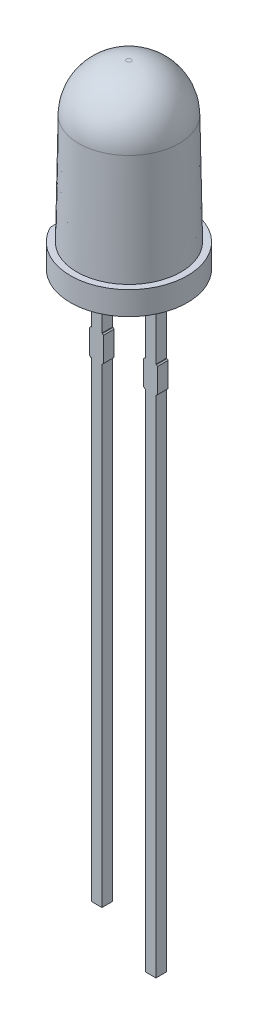
SolidWorks part; units mm, degrees
ref_plane "Front Plane" through (0, 0, 0) normal (0, 0, 1) x (1, 0, 0)
ref_plane "Top Plane" through (0, 0, 0) normal (0, 1, 0) x (1, 0, 0)
ref_plane "Right Plane" through (0, 0, 0) normal (1, 0, 0) x (0, 0, -1)
sketch "Sketch1" plane through (0, 0, 0) normal (0, 1, 0) x (1, 0, 0)
  circle A0 centre (0, 0) radius 2.75
  dimension "D1" = 5.5
extrude "Boss-Extrude1" add sketch "Sketch1" along normal blind 1.1 contours A0
sketch "Sketch2" plane through (0, 1.1, 0) normal (0, 1, 0) x (1, 0, 0)
  circle A0 centre (0, 0) radius 2.45
  dimension "D1" = 4.9
ref_plane "Plane1" through (0, 8.5, 0) normal (0, -1, 0) x (-1, 0, 0)
sketch "Sketch3" plane through (0, 0, 0) normal (0, 0, 1) x (1, 0, 0)
  line L0 (0, 1.1) -> (0, 8.5)
  line L2 (-3.025, 8.5) -> (3.025, 8.5) construction
sweep "Sweep1" add profiles "Sketch2" path "Sketch3"
draft "Draft1" type of draft neutral plane draft angle 1 faces to draft 1 face at (0, 8.5, 2.45) neutral plane through (0, 1.1, 0) neutral plane normal (0, 1, 0) parameters "D1"=1
fillet "Fillet1" radius 2.25 1 edges at (0, 8.5, 2.3208)
sketch "Sketch5" plane through (0, 1.1, 0) normal (0, 1, 0) x (1, 0, 0)
  line L0 (-2.45, 1.249) -> (-2.45, -1.249)
  circle A1 centre (0, 0) radius 2.45 construction
  circle A2 centre (0, 0) radius 2.75 construction
  arc A3 (-2.45, 1.249) -> (-2.45, -1.249) centre (0, 0) ccw
extrude "Cut-Extrude1" cut sketch "Sketch5" against normal blind 1.1
sketch "Sketch6" plane through (0, 0, 0) normal (0, -1, 0) x (1, 0, 0)
  line L0 (-2.2943, 0) -> (2.578, 0) construction
  line L1 (-1.52, 0.25) -> (-1.02, 0.25)
  line L2 (-1.52, 0.25) -> (-1.52, -0.25)
  line L3 (-1.52, -0.25) -> (-1.02, -0.25)
  line L4 (-1.02, 0.25) -> (-1.02, -0.25)
  line L5 (-1.52, 0.25) -> (-1.02, -0.25) construction
  line L6 (-1.52, -0.25) -> (-1.02, 0.25) construction
  line L7 (1.02, 0.25) -> (1.52, 0.25)
  line L8 (1.02, 0.25) -> (1.02, -0.25)
  line L9 (1.02, -0.25) -> (1.52, -0.25)
  line L10 (1.52, 0.25) -> (1.52, -0.25)
  line L11 (1.02, 0.25) -> (1.52, -0.25) construction
  line L12 (1.02, -0.25) -> (1.52, 0.25) construction
  line L13 (0, 1.1407) -> (0, -1.4584) construction
  point P0 (-1.27, 0)
  point P5 (1.27, 0)
  dimension "D1" = 0.5
  dimension "D2" = 0.5
  dimension "D3" = 2.54
extrude "Boss-Extrude2" add sketch "Sketch6" along normal blind 28
other "Move Face1" face at (-1.27, -28, 0) parameters "D1"=1.6
sketch "Sketch7" plane through (0, 0, 0.25) normal (0, 0, 1) x (1, 0, 0)
  line L0 (1.52, -28) -> (1.02, -28) construction
  line L1 (0.945, -3) -> (1.595, -3)
  line L2 (0.945, -3) -> (0.945, -4.25)
  line L3 (0.945, -4.25) -> (1.595, -4.25)
  line L4 (1.595, -3) -> (1.595, -4.25)
  line L5 (-1.595, -3) -> (-0.945, -3)
  line L6 (-1.595, -3) -> (-1.595, -4.25)
  line L7 (-1.595, -4.25) -> (-0.945, -4.25)
  line L8 (-0.945, -3) -> (-0.945, -4.25)
  line L9 (1.27, 0) -> (1.27, -5.5864) construction
  line L10 (1.52, 0) -> (1.02, 0) construction
  line L11 (-1.27, 0) -> (-1.27, -8.0728) construction
  line L12 (-1.02, 0) -> (-1.52, 0) construction
  dimension "D1" = 25
  dimension "D2" = 23.75
  dimension "D3" = 0.65
extrude "Boss-Extrude3" add sketch "Sketch7" against normal up to surface (0.5 mm away) up to face at (1.27, -14, -0.25)
chamfer "Chamfer1" distance 0.05 angle 45 8 edges at (1.595, -4.25, 0) (1.595, -3, 0) (0.945, -3, 0) (0.945, -4.25, 0) (-0.945, -4.25, 0) (-0.945, -3, 0) (-1.595, -4.25, 0) (-1.595, -3, 0)
